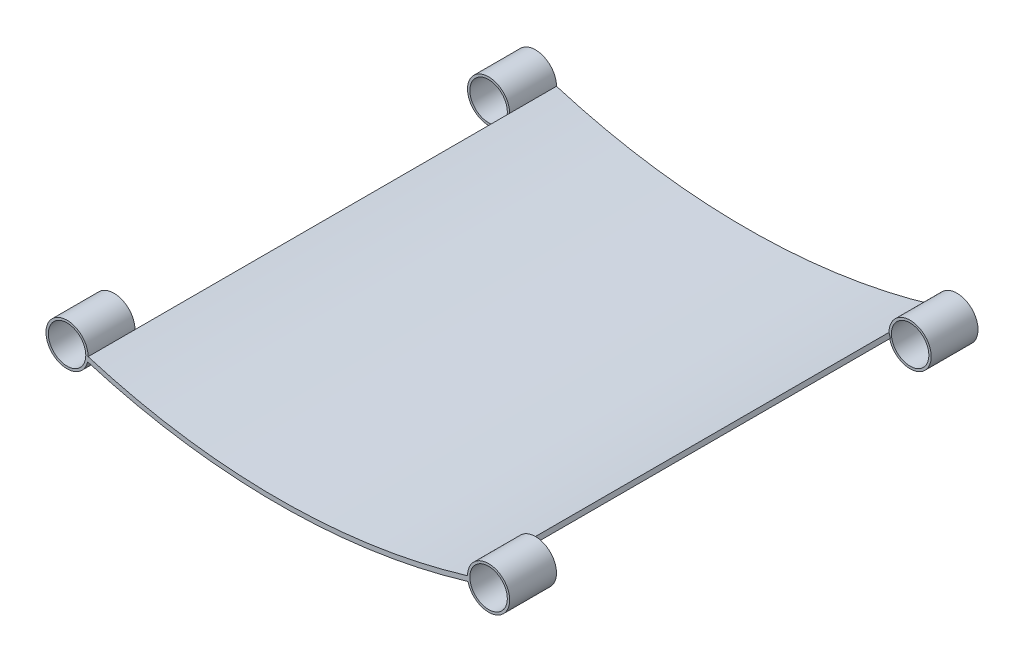
SolidWorks part; units mm, degrees
ref_plane "Front Plane" through (0, 0, 0) normal (0, 0, 1) x (1, 0, 0)
ref_plane "Top Plane" through (0, 0, 0) normal (0, 1, 0) x (1, 0, 0)
ref_plane "Right Plane" through (0, 0, 0) normal (1, 0, 0) x (0, 0, -1)
sketch "Sketch1" plane through (0, 0, 0) normal (0, 0, 1) x (1, 0, 0)
  circle A0 centre (-45, 0) radius 4
  circle A1 centre (-45, 0) radius 4.5
  circle A2 centre (45, 0) radius 4
  circle A3 centre (45, 0) radius 4.5
  point P4 (0, 0)
  dimension "D1" = 9
  dimension "D2" = 8
  dimension "D3" = 9
  dimension "D4" = 8
  dimension "D5" = 45
  dimension "D6" = 90
extrude "Boss-Extrude1" add sketch "Sketch1" against normal blind 10
sketch "Sketch2" plane through (0, 0, 0) normal (0, 0, 1) x (1, 0, 0)
  line L0 (-40.5, 0) -> (-40.7893, -0.9572)
  line L1 (40.5, 0) -> (40.7893, -0.9572)
  arc A0 (40.5, 0) -> (-40.5, 0) centre (0, 134.014) cw
  circle A3 centre (45, 0) radius 4.5 construction
  circle A4 centre (-45, 0) radius 4.5 construction
  arc A5 (40.7893, -0.9572) -> (-40.7893, -0.9572) centre (0, 134.014) cw
  point P3 (-35.5, 0)
  point P8 (35.5, 0)
  point P12 (-40.5, 0)
  dimension "D1" = 140
  dimension "D2" = 1
extrude "Boss-Extrude4" add sketch "Sketch2" against normal blind 100 contours A0 L0 A5 L1
sketch "Sketch4" plane through (0, 0, -100) normal (0, 0, -1) x (-1, 0, 0)
  circle A0 centre (45, 0) radius 4 construction
  circle A1 centre (-45, 0) radius 4 construction
  circle A2 centre (45, 0) radius 4
  circle A3 centre (-45, 0) radius 4
  circle A4 centre (45, 0) radius 4.5
  circle A5 centre (-45, 0) radius 4.5
  dimension "D1" = 9
  dimension "D2" = 9
extrude "Boss-Extrude5" add sketch "Sketch4" against normal blind 10
